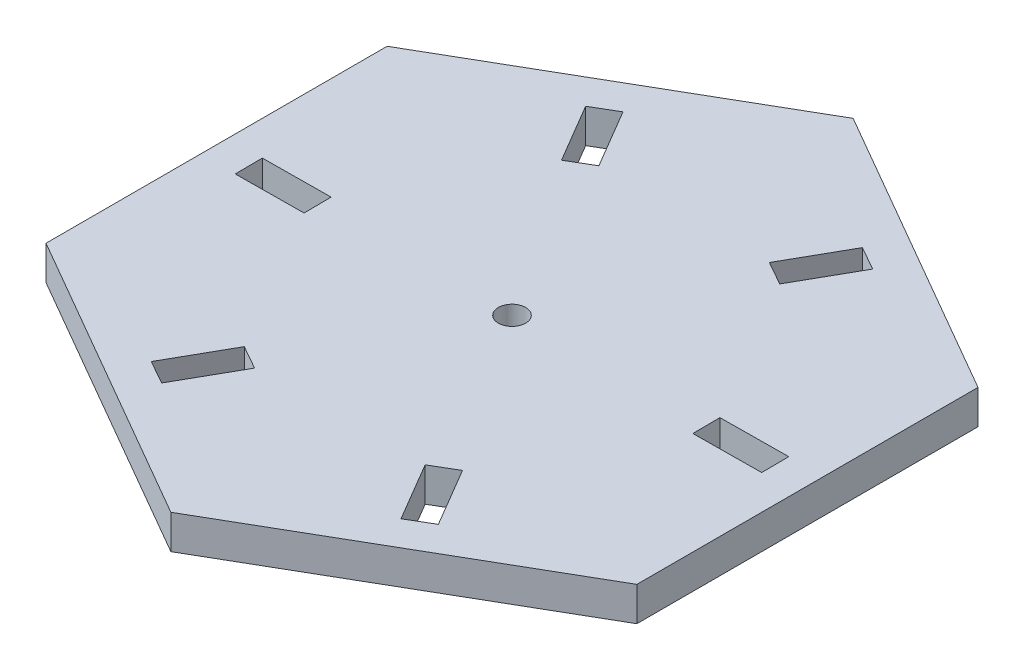
SolidWorks part; units mm, degrees
ref_plane "Front Plane" through (0, 0, 0) normal (0, 0, 1) x (1, 0, 0)
ref_plane "Top Plane" through (0, 0, 0) normal (0, 1, 0) x (1, 0, 0)
ref_plane "Right Plane" through (0, 0, 0) normal (1, 0, 0) x (0, 0, -1)
sketch "Sketch1" plane through (0, 0, 0) normal (0, 1, 0) x (1, 0, 0)
  line L0 (-11.1677, 18.9513) -> (-13.4889, 22.8903) construction
  line L1 (27.4963, 15.875) -> (0, 31.75)
  line L2 (0, 31.75) -> (-27.4963, 15.875)
  line L3 (-27.4963, 15.875) -> (-27.4963, -15.875)
  line L4 (-27.4963, -15.875) -> (0, -31.75)
  line L5 (0, -31.75) -> (27.4963, -15.875)
  line L6 (27.4963, -15.875) -> (27.4963, 15.875)
  line L7 (21.8831, 12.8954) -> (-0.2262, 25.399)
  line L8 (-0.2262, 25.399) -> (-22.1093, 12.5036)
  line L9 (-22.1093, 12.5036) -> (-21.8831, -12.8954)
  line L10 (-21.8831, -12.8954) -> (0.2262, -25.399)
  line L11 (0.2262, -25.399) -> (22.1093, -12.5036)
  line L12 (22.1093, -12.5036) -> (21.8831, 12.8954)
  line L13 (-13.4224, 20.276) -> (-11.2341, 21.5656)
  line L14 (-11.2341, 21.5656) -> (-8.0103, 16.0948)
  line L15 (-8.0103, 16.0948) -> (-10.1986, 14.8053)
  line L16 (-10.1986, 14.8053) -> (-13.4224, 20.276)
  line L17 (7.7224, 16.2349) -> (10.8483, 21.7622)
  line L18 (10.8483, 21.7622) -> (13.0593, 20.5118)
  line L19 (13.0593, 20.5118) -> (9.9333, 14.9845)
  line L20 (9.9333, 14.9845) -> (7.7224, 16.2349)
  line L21 (17.921, 1.4296) -> (24.2708, 1.4862)
  line L22 (24.2708, 1.4862) -> (24.2934, -1.0537)
  line L23 (24.2934, -1.0537) -> (17.9436, -1.1103)
  line L24 (17.9436, -1.1103) -> (17.921, 1.4296)
  line L25 (10.1986, -14.8053) -> (13.4224, -20.276)
  line L26 (13.4224, -20.276) -> (11.2341, -21.5656)
  line L27 (11.2341, -21.5656) -> (8.0103, -16.0948)
  line L28 (8.0103, -16.0948) -> (10.1986, -14.8053)
  line L29 (-7.7224, -16.2349) -> (-10.8483, -21.7622)
  line L30 (-10.8483, -21.7622) -> (-13.0593, -20.5118)
  line L31 (-13.0593, -20.5118) -> (-9.9333, -14.9845)
  line L32 (-9.9333, -14.9845) -> (-7.7224, -16.2349)
  line L33 (-17.921, -1.4296) -> (-24.2708, -1.4862)
  line L34 (-24.2708, -1.4862) -> (-24.2934, 1.0537)
  line L35 (-24.2934, 1.0537) -> (-17.9436, 1.1103)
  line L36 (-17.9436, 1.1103) -> (-17.921, -1.4296)
  circle A0 centre (0, 0) radius 27.4963 construction
  circle A1 centre (0, 0) radius 21.997 construction
  circle A2 centre (0, 0) radius 1.27
  point P21 (-12.3283, 20.9208)
  point P24 (-11.8105, 17.5406)
  point P47 (0, 0)
  dimension "D5" = 2.54
  dimension "D9" = 2.54
  dimension "D1" = 31.75
  dimension "D2" = 25.4
  dimension "D3" = 25.399
  dimension "D4" = 6.355
  dimension "D6" = 6.35
  dimension "D7" = 0.889
  dimension "D10" = 16.2349
  dimension "D11" = 29.7909
  dimension "D8" = 6
extrude "Boss-Extrude1" add sketch "Sketch1" against normal blind 3.175 contours L11 L12 L7 L8 L9 L10 A2 | L5 L6 L1 L2 L3 L4 L12 L11 L10 L9 L8 L7
